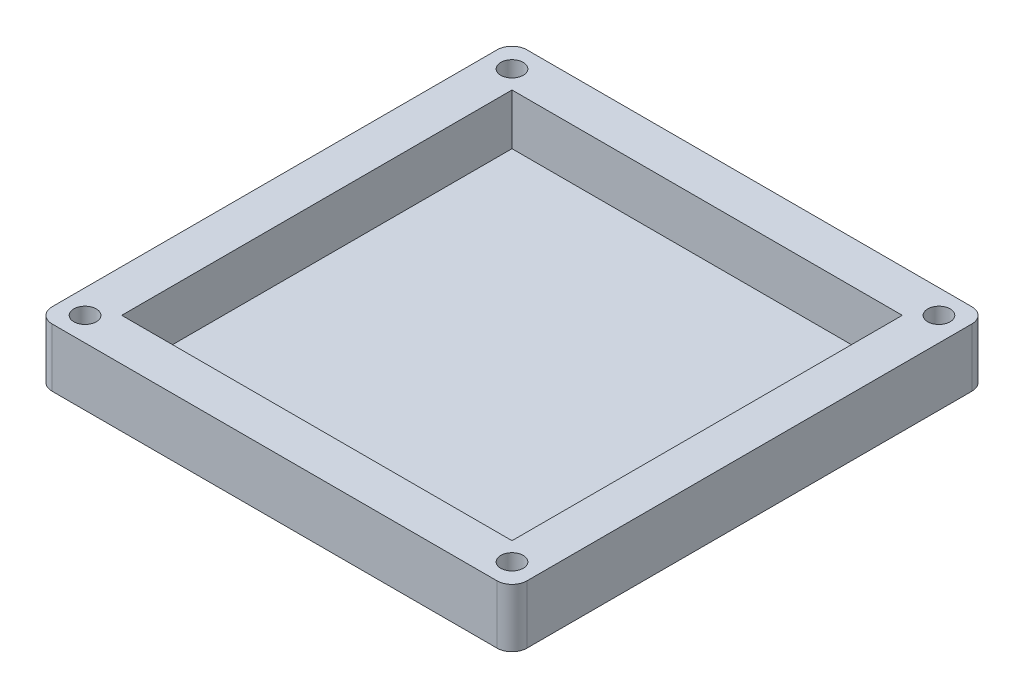
SolidWorks part; units mm, degrees
ref_plane "Front Plane" through (0, 0, 0) normal (0, 0, 1) x (1, 0, 0)
ref_plane "Top Plane" through (0, 0, 0) normal (0, 1, 0) x (1, 0, 0)
ref_plane "Right Plane" through (0, 0, 0) normal (1, 0, 0) x (0, 0, -1)
sketch "Sketch1" plane through (0, 0, 0) normal (0, 1, 0) x (1, 0, 0)
  line L1 (0, 0) -> (63.5, 0)
  line L2 (0, 0) -> (0, 63.5)
  line L3 (0, 63.5) -> (63.5, 63.5)
  line L4 (63.5, 0) -> (63.5, 63.5)
  dimension "D1" = 63.5
extrude "Boss-Extrude1" add sketch "Sketch1" along normal blind 7.8
sketch "Sketch2" plane through (0, 7.8, 0) normal (0, 1, 0) x (1, 0, 0)
  line L0 (0, 63.5) -> (0, 0) construction
  line L1 (5.65, 5.65) -> (57.85, 5.65)
  line L2 (5.65, 5.65) -> (5.65, 57.85)
  line L3 (5.65, 57.85) -> (57.85, 57.85)
  line L4 (57.85, 5.65) -> (57.85, 57.85)
  line L5 (63.5, 63.5) -> (0, 63.5) construction
  line L7 (63.5, 0) -> (63.5, 63.5) construction
  line L8 (0, 0) -> (63.5, 0) construction
  dimension "D1" = 5.65
  dimension "D2" = 5.65
  dimension "D3" = 5.65
  dimension "D4" = 5.65
extrude "Cut-Extrude1" cut sketch "Sketch2" against normal blind 6.8
sketch "Sketch3" plane through (0, 7.8, 0) normal (0, 1, 0) x (1, 0, 0)
  line L0 (63.5, 63.5) -> (0, 63.5) construction
  line L1 (0, 63.5) -> (0, 0) construction
  line L2 (63.5, 0) -> (63.5, 63.5) construction
  line L3 (0, 0) -> (63.5, 0) construction
  circle A0 centre (3.2, 3.2) radius 1.5
  circle A1 centre (3.2, 60.3) radius 1.5
  circle A2 centre (60.3, 60.3) radius 1.5
  circle A3 centre (60.3, 3.2) radius 1.5
  dimension "D1" = 3
  dimension "D2" = 3.2
  dimension "D3" = 3.2
  dimension "D4" = 3.2
  dimension "D5" = 3.2
  dimension "D6" = 3.2
  dimension "D7" = 3.2
  dimension "D8" = 3.2
  dimension "D9" = 3.2
extrude "Cut-Extrude2" cut sketch "Sketch3" against normal blind 7.5
fillet "Fillet1" radius 2 4 edges at (0, 3.9, -63.5) (63.5, 3.9, -63.5) (63.5, 3.9, 0) (0, 3.9, 0)
